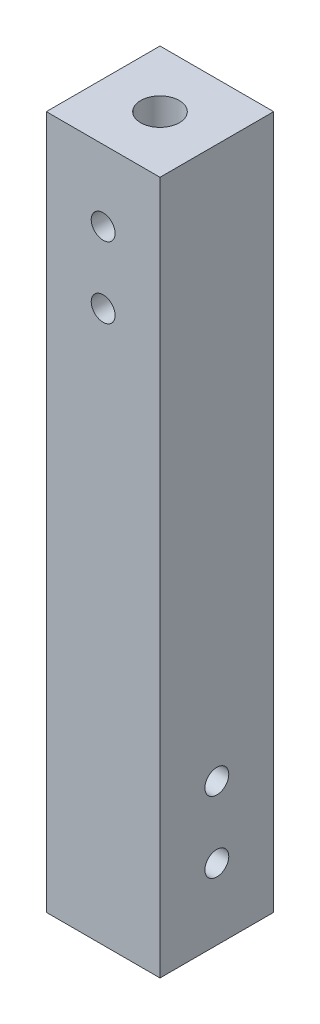
SolidWorks part; units mm, degrees
ref_plane "Front" through (0, 0, 0) normal (0, 0, 1) x (1, 0, 0)
ref_plane "Top" through (0, 0, 0) normal (0, 1, 0) x (1, 0, 0)
ref_plane "Right" through (0, 0, 0) normal (1, 0, 0) x (0, 0, -1)
sketch "Sketch1" plane through (0, 0, 0) normal (0, 1, 0) x (1, 0, 0)
  line L1 (0, 0) -> (20, 0)
  line L2 (0, 0) -> (0, 20)
  line L3 (0, 20) -> (20, 20)
  line L4 (20, 0) -> (20, 20)
  dimension "D1" = 20
  dimension "D2" = 20
extrude "Boss-Extrude1" add sketch "Sketch1" along normal blind 122
hole_wizard "M8 Tapped Hole1" positions "Sketch4" profile "Sketch5" tap size "M8" standard "ISO"
sketch "Sketch4" plane through (0, 122, 0) normal (0, 1, 0) x (1, 0, 0)
  line L0 (0, 20) -> (20, 0) construction
  line L2 (0, 0) -> (20, 20) construction
  point P13 (10, 10)
sketch "Sketch5" plane through (10, 122, -10) normal (1, 0, 0) x (0, 0, 1)
  line L0 (0, 0) -> (0, 21.7929)
  line L1 (0, 21.7929) -> (3.4, 19.75)
  line L2 (3.4, 19.75) -> (3.4, 0)
  line L5 (3.4, 0) -> (0, 0)
  line L10 (0, 21.7929) -> (-3.4, 19.75) construction
  line L11 (0, -6.35) -> (0, 107.95) construction
  dimension "Tap Drill Dia." = 6.8
  dimension "Tap Drill Depth" = 19.75
  dimension "Drill Angle" = 118
cosmetic thread "Hole Thread1" parameters "D1"=16, "D2"=8
ref_plane "Plane1" through (0, 61, 0) normal (0, 1, 0) x (1, 0, 0)
mirror "Mirror1" about plane through (0, 61, 0) normal (0, 1, 0) of "M8 Tapped Hole1"
cosmetic thread "Hole Thread2" parameters "D1"=16, "D2"=8
hole_wizard "M5 Tapped Hole1" positions "Sketch6" profile "Sketch7" tap size "M5" standard "ISO"
sketch "Sketch6" plane through (0, 0, 0) normal (0, 0, 1) x (1, 0, 0)
  line L0 (10, 122) -> (10, 95.0401) construction
  line L1 (0, 122) -> (20, 122) construction
  point P0 (10, 97)
  point P7 (10, 109.5)
  dimension "D1" = 25
  dimension "D2" = 12.5
sketch "Sketch7" plane through (10, 97, 0) normal (1, 0, 0) x (0, -1, 0)
  line L0 (0, 0) -> (0, 13.6618)
  line L1 (0, 13.6618) -> (2.1, 12.4)
  line L2 (2.1, 12.4) -> (2.1, 0)
  line L5 (2.1, 0) -> (0, 0)
  line L10 (0, 13.6618) -> (-2.1, 12.4) construction
  line L11 (0, -6.35) -> (0, 107.95) construction
  dimension "Tap Drill Dia." = 4.2
  dimension "Tap Drill Depth" = 12.4
  dimension "Drill Angle" = 118
cosmetic thread "Hole Thread3"
cosmetic thread "Hole Thread5"
hole_wizard "M5 Tapped Hole2" positions "Sketch8" profile "Sketch9" tap size "M5" standard "ISO"
sketch "Sketch8" plane through (20, 0, 0) normal (1, 0, 0) x (0, 0, -1)
  line L0 (10, 0) -> (10, 25) construction
  line L1 (0, 0) -> (20, 0) construction
  point P7 (10, 25)
  point P8 (10, 12.5)
  dimension "D1" = 25
  dimension "D2" = 12.5
sketch "Sketch9" plane through (20, 12.5, -10) normal (0, 1, 0) x (0, 0, -1)
  line L0 (0, 0) -> (0, 13.6618)
  line L1 (0, 13.6618) -> (2.1, 12.4)
  line L2 (2.1, 12.4) -> (2.1, 0)
  line L5 (2.1, 0) -> (0, 0)
  line L10 (0, 13.6618) -> (-2.1, 12.4) construction
  line L11 (0, -6.35) -> (0, 107.95) construction
  dimension "Tap Drill Dia." = 4.2
  dimension "Tap Drill Depth" = 12.4
  dimension "Drill Angle" = 118
cosmetic thread "Hole Thread4"
cosmetic thread "Hole Thread6"
